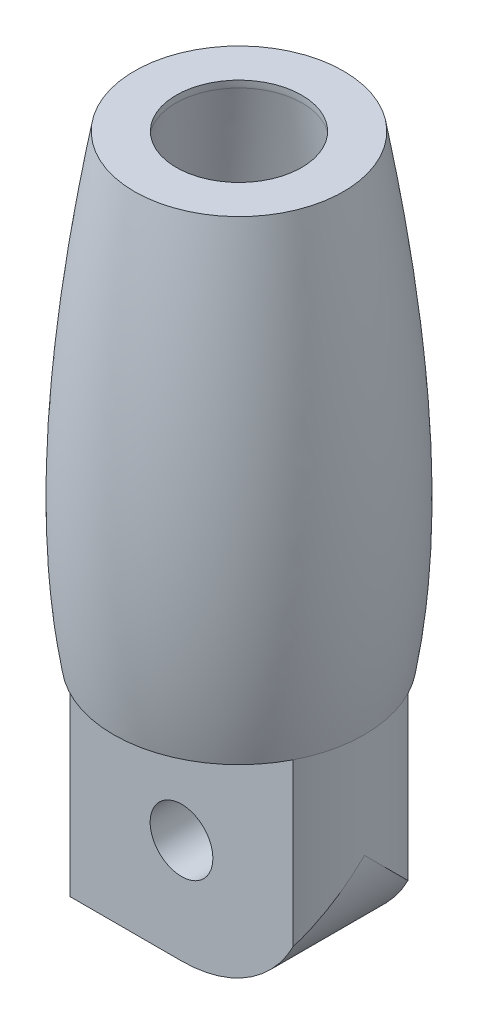
SolidWorks part; units mm, degrees
ref_plane "Front Plane" through (0, 0, 0) normal (0, 0, 1) x (1, 0, 0)
ref_plane "Top Plane" through (0, 0, 0) normal (0, 1, 0) x (1, 0, 0)
ref_plane "Right Plane" through (0, 0, 0) normal (1, 0, 0) x (0, 0, -1)
sketch "Sketch1" plane through (0, 0, 0) normal (1, 0, 0) x (0, 0, -1)
  line L0 (0, 0) -> (0, 22)
  line L1 (0, 0) -> (6, 0)
  line L2 (0, 22) -> (5, 22)
  line L3 (10.2073, -7.5319) -> (0.4768, 47.6525) construction
  line L4 (0, 2) -> (4.2698, 2)
  spline S0 degree 2 poles (5, 22) (7.4326, 8.2039) (6, 0) knots 0 0 0 1 1 1
  spline S1 degree 1 poles (3.0304, 21.6527) (4.0298, 0.344) knots 0 0 1 1 construction
  spline S2 degree 2 poles (3.0304, 21.6527) (3.7256, 17.7097) (4.8385, 7.3414) (4.2718, 1.9954) (4.1357, 0.9419) (4.0298, 0.344) knots 0 0 0 0.289998 0.869994 0.921996 1 1 1 only from (3.0304, 21.6527) to (4.2698, 2)
  spline S3 degree 2 poles (3.0304, 21.6527) (3.0169, 21.7293) (3, 22) knots 0 0 0 1 1 1
  dimension "D4" = 100
  dimension "D5" = 2
  dimension "D6" = 2
  dimension "D1" = 22
  dimension "D2" = 5
  dimension "D3" = 6
  dimension "D7" = 2
revolve "Revolve1" add sketch "Sketch1" angle 360 about L0
sketch "Sketch3" plane through (0, 0, 0) normal (0, 0, 1) x (1, 0, 0)
  line L0 (-6, 0) -> (-6, -11)
  line L1 (-6, -11) -> (0, -11)
  line L2 (-6, 0) -> (6, 0)
  line L3 (6, 0) -> (6, -5)
  arc A0 (0, -11) -> (6, -5) centre (0, -5) ccw
  dimension "D1" = 11
  dimension "D2" = 5
extrude "Boss-Extrude1" add sketch "Sketch3" along normal mid plane 5.5
sketch "Sketch5" plane through (0, 0, 0) normal (0, 0, 1) x (1, 0, 0)
  line L1 (-6, -11) -> (0, -11) construction
  circle A1 centre (0, -6) radius 1.5
  dimension "D3" = 5
extrude "Cut-Extrude5" cut sketch "Sketch5" against normal blind 14 and the other way blind 14
sketch "Sketch6" plane through (0, 0, 0) normal (0, 1, 0) x (1, 0, 0)
  circle A0 centre (0, 0) radius 6
  arc A1 (-5.3327, 2.75) -> (-6, 0) centre (0, 0) ccw construction
extrude "Cut-Extrude6" cut sketch "Sketch6" against normal through all flip side to cut
sketch "Sketch7" plane through (0, -11, 0) normal (0, -1, 0) x (1, 0, 0)
  line L0 (0, 0) -> (6, 0) construction
  circle A0 centre (3, 0) radius 1
  arc A1 (5.3327, -2.75) -> (5.3327, 2.75) centre (0, 0) ccw construction
  point P8 (0, 0)
  point P9 (3, 0)
  dimension "D1" = 2
extrude "Cut-Extrude7" cut sketch "Sketch7" against normal blind 20
ref_plane "Plane1" through (-6, 0, 0) normal (-1, 0, 0) x (0, 0, 1)
sketch "Sketch8" plane through (-6, 0, 0) normal (-1, 0, 0) x (0, 0, 1)
  line L0 (0, 0) -> (0, -11) construction
  circle A0 centre (0, -5.5) radius 1
  point P5 (0, 0)
  point P6 (0, -5.5)
  point P7 (0, 0)
  point P9 (0, 0)
  dimension "D1" = 2
sketch "Sketch10" plane through (0, 0, 0) normal (0, 0, 1) x (1, 0, 0)
  line L0 (-6, 0) -> (-6, -11) construction
  line L1 (-6, -5.5) -> (-2.3327, -5.5) construction
  line L3 (-2.3327, -5.5) -> (-2.3327, 2) construction
  line L6 (-5.3327, 0) -> (-5.3327, -11) construction
  line L7 (4, 2) -> (2, 2) construction
  spline S0 degree 2 poles (-6, -5.5) (-2.3327, -5.5) (-2.3327, 2) knots 0 0 0 1 1 1
  point P4 (0, 0)
  point P7 (-2.3327, 3.2885)
  point P10 (-2.3327, 0)
  dimension "D1" = 3
sweep "Cut-Sweep1" cut profiles "Sketch8" path "Sketch10"
